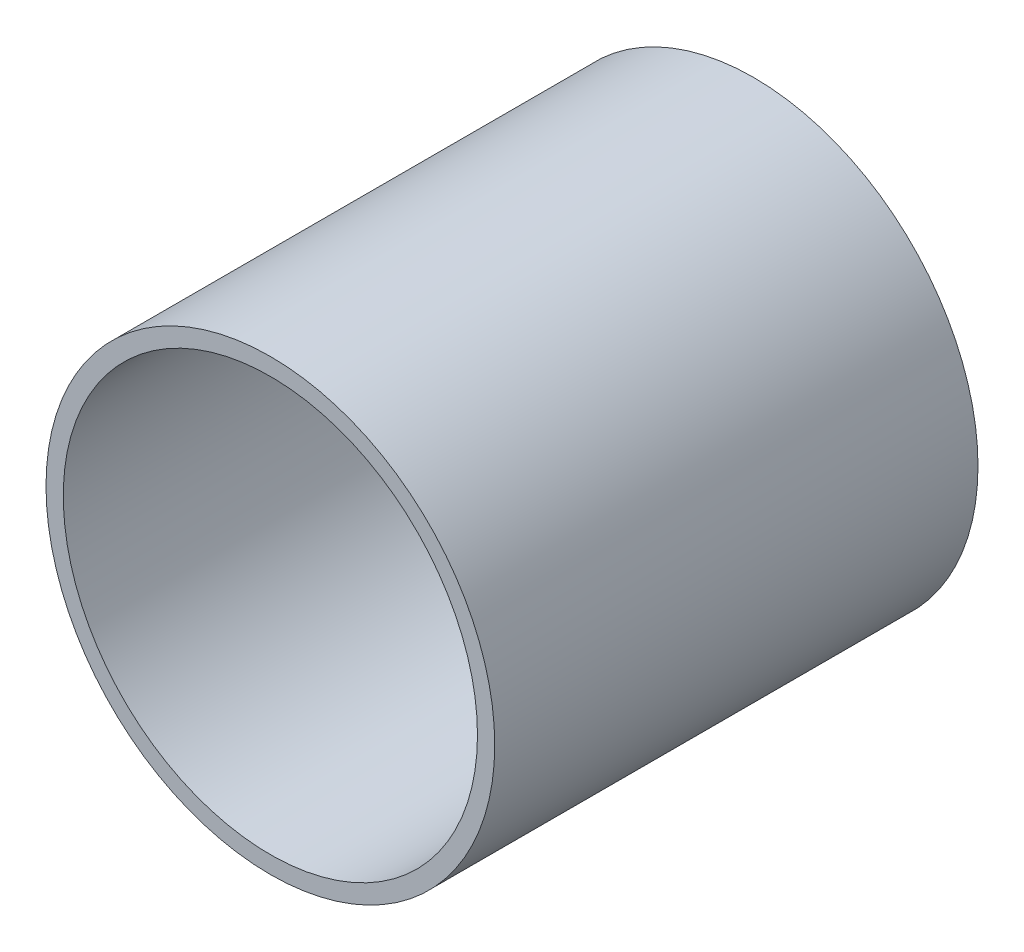
SolidWorks part; units mm, degrees
ref_plane "Front Plane" through (0, 0, 0) normal (0, 0, 1) x (1, 0, 0)
ref_plane "Top Plane" through (0, 0, 0) normal (0, 1, 0) x (1, 0, 0)
ref_plane "Right Plane" through (0, 0, 0) normal (1, 0, 0) x (0, 0, -1)
sketch "Sketch1" plane through (0, 0, 0) normal (0, 0, 1) x (1, 0, 0)
  circle A0 centre (0, 0) radius 30
  circle A1 centre (0, 0) radius 32.5
  dimension "D1" = 60
  dimension "D2" = 65
extrude "Boss-Extrude1" add sketch "Sketch1" along normal blind 70
